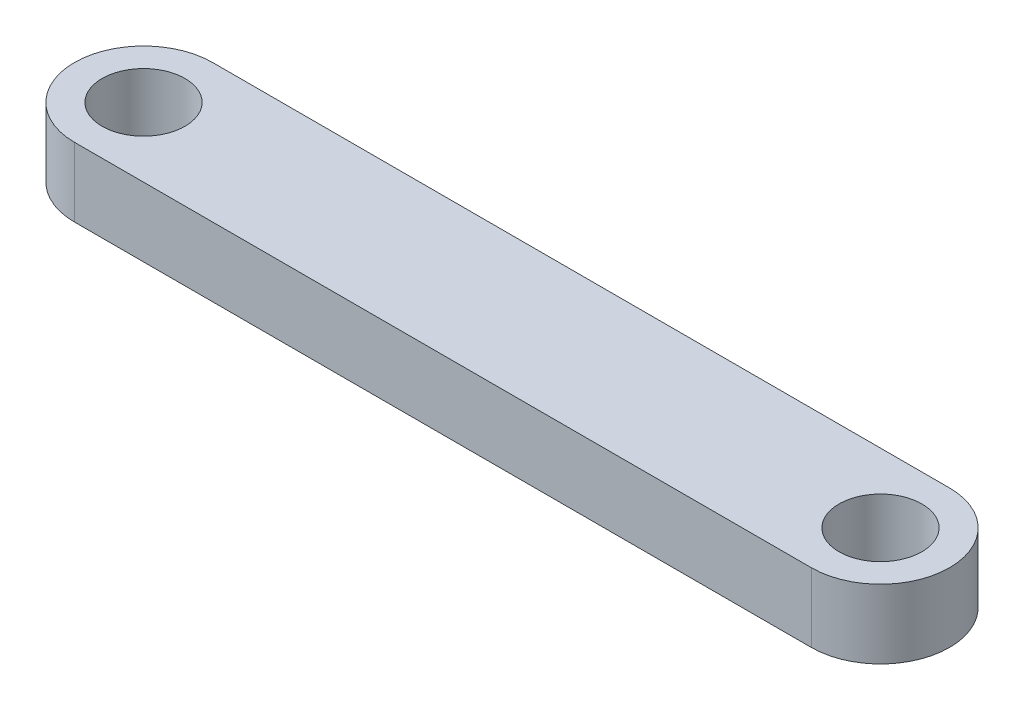
SolidWorks part; units mm, degrees
ref_plane "Front Plane" through (0, 0, 0) normal (0, 0, 1) x (1, 0, 0)
ref_plane "Top Plane" through (0, 0, 0) normal (0, 1, 0) x (1, 0, 0)
ref_plane "Right Plane" through (0, 0, 0) normal (1, 0, 0) x (0, 0, -1)
sketch "Sketch1" plane through (0, 0, 0) normal (0, 1, 0) x (1, 0, 0)
  line L0 (0, 0) -> (-32, 0) construction
  line L1 (0, -3) -> (-32, -3)
  line L2 (0, 3) -> (-32, 3)
  arc A0 (0, -3) -> (0, 3) centre (0, 0) ccw
  arc A1 (-32, 3) -> (-32, -3) centre (-32, 0) ccw
  circle A2 centre (-32, 0) radius 1.8
  circle A3 centre (0, 0) radius 1.8
  point P3 (-16, 0)
  dimension "D1" = 3
  dimension "D3" = 3.6
  dimension "D2" = 32
extrude "Boss-Extrude1" add sketch "Sketch1" along normal blind 3
